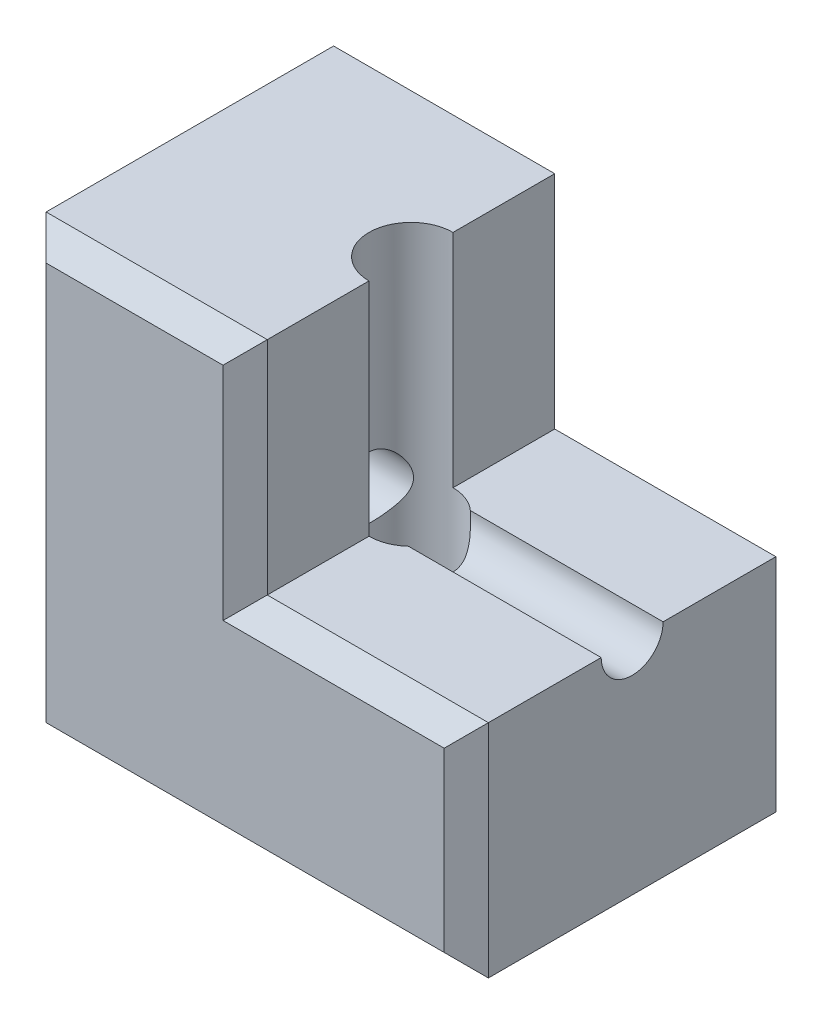
SolidWorks part; units mm, degrees
ref_plane "Front Plane" through (0, 0, 0) normal (0, 0, 1) x (1, 0, 0)
ref_plane "Top Plane" through (0, 0, 0) normal (0, 1, 0) x (1, 0, 0)
ref_plane "Right Plane" through (0, 0, 0) normal (1, 0, 0) x (0, 0, -1)
sketch "Sketch2" plane through (0, 0, 0) normal (0, 0, 1) x (1, 0, 0)
  line L0 (0, 20) -> (0, 0)
  line L1 (0, 0) -> (20, 0)
  line L2 (20, 0) -> (20, 10)
  line L3 (20, 10) -> (10, 10)
  line L4 (10, 10) -> (10, 20)
  line L5 (10, 20) -> (0, 20)
  dimension "D1" = 20
  dimension "D2" = 10
extrude "Boss-Extrude2" add sketch "Sketch2" along normal blind 15
sketch "Sketch3" plane through (0, 0, 0) normal (-1, 0, 0) x (0, 0, 1)
  line L0 (15, 20) -> (0, 20) construction
  circle A0 centre (7.5, 10) radius 1.4
  point P4 (7.5, 20)
  dimension "D1" = 2.8
extrude "Cut-Extrude1" cut sketch "Sketch3" against normal through all
ref_plane "Plane1" through (0, 3, 0) normal (0, -1, 0) x (-1, 0, 0)
sketch "Sketch4" plane through (0, 3, 0) normal (0, -1, 0) x (-1, 0, 0)
  line L0 (-20, -15) -> (-20, 0) construction
  circle A0 centre (-10, -7.5) radius 1.9
  point P7 (-20, -7.5)
  dimension "D1" = 3.8
extrude "Cut-Extrude2" cut sketch "Sketch4" against normal through all both and the other way through all
sketch "Sketch5" plane through (0, 3, 0) normal (0, -1, 0) x (-1, 0, 0)
  line L0 (-12.75, -3) -> (-13.5538, 0)
  line L1 (-12.75, -12) -> (-7.25, -12)
  line L2 (-12.75, -12) -> (-12.75, -3)
  line L3 (-12.75, -3) -> (-7.25, -3) construction
  line L4 (-7.25, -12) -> (-7.25, -3)
  line L5 (-10, -3) -> (-10, -12) construction
  line L6 (-12.75, -7.5) -> (-7.25, -7.5) construction
  line L7 (-13.5538, 0) -> (-6.4462, 0)
  line L8 (-6.4462, 0) -> (-7.25, -3)
  point P0 (-10, -7.5)
  dimension "D1" = 5.5
  dimension "D2" = 9
  dimension "D3" = 15
extrude "Cut-Extrude3" cut sketch "Sketch5" against normal blind 3
chamfer "Chamfer1" distance 1 angle 45 2 edges at (10, 3, 0) (10, 6, 0)
chamfer "Chamfer2" distance 1 angle 45 6 edges at (10, 15, 15) (15, 10, 15) (20, 5, 15) (10, 0, 15) (0, 10, 15) (5, 20, 15)
chamfer "Chamfer5" distance 1 angle 45 6 edges at (20, 5, 0) (10, 0, 0) (0, 10, 0) (5, 20, 0) (10, 15, 0) (15, 10, 0)
